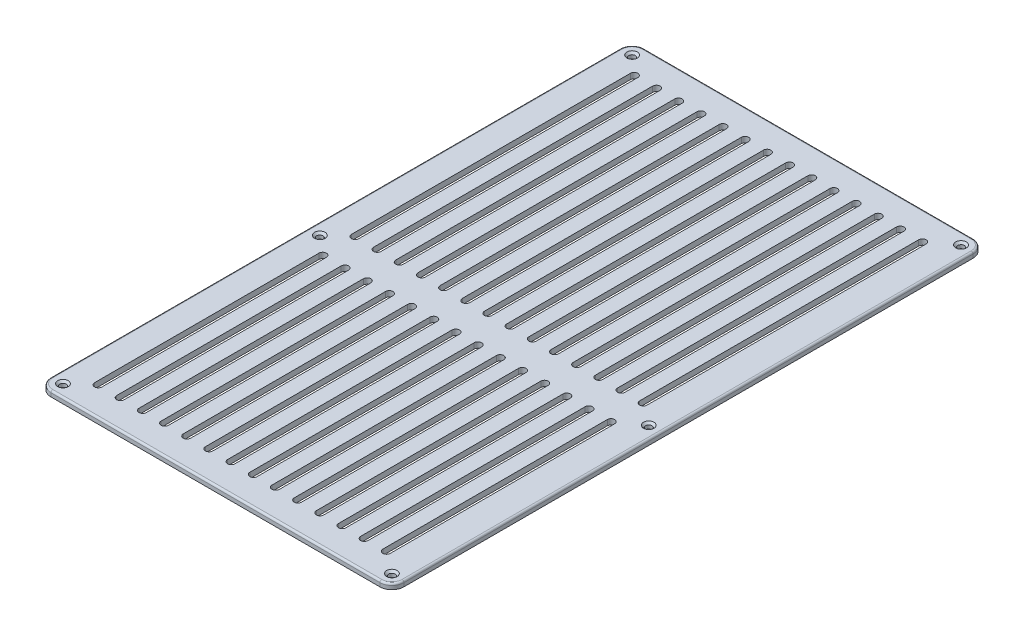
SolidWorks part; units mm, degrees
ref_plane "Front Plane" through (0, 0, 0) normal (0, 0, 1) x (1, 0, 0)
ref_plane "Top Plane" through (0, 0, 0) normal (0, 1, 0) x (1, 0, 0)
ref_plane "Right Plane" through (0, 0, 0) normal (1, 0, 0) x (0, 0, -1)
sketch "Sketch1" plane through (0, 0, 0) normal (0, 1, 0) x (1, 0, 0)
  line L0 (0, 7) -> (0, 315)
  line L1 (7, 322) -> (185, 322)
  line L2 (192, 315) -> (192, 7)
  line L3 (185, 0) -> (7, 0)
  arc A0 (192, 7) -> (185, 0) centre (185, 7) cw
  arc A1 (0, 7) -> (7, 0) centre (7, 7) ccw
  arc A2 (185, 322) -> (192, 315) centre (185, 315) cw
  arc A3 (0, 315) -> (7, 322) centre (7, 315) cw
  circle A4 centre (7, 315) radius 1.75
  circle A5 centre (185, 315) radius 1.75
  circle A6 centre (185, 7) radius 1.75
  circle A7 centre (7, 7) radius 1.75
  circle A8 centre (7, 146) radius 1.75
  circle A9 centre (185, 146) radius 1.75
  point P9 (0, 0)
  dimension "D1" = 7
extrude "Boss-Extrude1" add sketch "Sketch1" along normal blind 3
chamfer "Chamfer1" distance 1.1 angle 45 6 edges at (7, 3, -313.25) (7, 3, -144.25) (7, 3, -5.25) (185, 3, -5.25) (185, 3, -144.25) (185, 3, -313.25)
sketch "Sketch2" plane through (0, 3, 0) normal (0, 1, 0) x (1, 0, 0)
  line L0 (31.1, 306) -> (31.1, 155)
  line L10 (27.1, 306) -> (27.1, 155)
  line L15 (31.1, 16) -> (31.1, 137.46)
  line L16 (27.1, 16) -> (27.1, 137.46)
  line L26 (15.1, 306) -> (15.1, 155)
  line L28 (19.1, 306) -> (19.1, 155)
  line L29 (43.1, 306) -> (43.1, 155)
  line L30 (39.1, 306) -> (39.1, 155)
  line L31 (43.1, 16) -> (43.1, 137.46)
  line L33 (15.1, 16) -> (15.1, 137.46)
  line L35 (19.1, 16) -> (19.1, 137.46)
  line L36 (39.1, 16) -> (39.1, 137.46)
  line L37 (55.1, 306) -> (55.1, 155)
  line L38 (51.1, 306) -> (51.1, 155)
  line L39 (55.1, 16) -> (55.1, 137.46)
  line L40 (51.1, 16) -> (51.1, 137.46)
  line L41 (67.1, 306) -> (67.1, 155)
  line L42 (63.1, 306) -> (63.1, 155)
  line L43 (67.1, 16) -> (67.1, 137.46)
  line L44 (63.1, 16) -> (63.1, 137.46)
  line L45 (79.1, 306) -> (79.1, 155)
  line L46 (75.1, 306) -> (75.1, 155)
  line L47 (79.1, 16) -> (79.1, 137.46)
  line L48 (75.1, 16) -> (75.1, 137.46)
  line L49 (91.1, 306) -> (91.1, 155)
  line L50 (87.1, 306) -> (87.1, 155)
  line L51 (91.1, 16) -> (91.1, 137.46)
  line L52 (87.1, 16) -> (87.1, 137.46)
  line L53 (103.1, 306) -> (103.1, 155)
  line L54 (99.1, 306) -> (99.1, 155)
  line L55 (103.1, 16) -> (103.1, 137.46)
  line L56 (99.1, 16) -> (99.1, 137.46)
  line L57 (115.1, 306) -> (115.1, 155)
  line L58 (111.1, 306) -> (111.1, 155)
  line L59 (115.1, 16) -> (115.1, 137.46)
  line L60 (111.1, 16) -> (111.1, 137.46)
  line L61 (127.1, 306) -> (127.1, 155)
  line L62 (123.1, 306) -> (123.1, 155)
  line L63 (127.1, 16) -> (127.1, 137.46)
  line L64 (123.1, 16) -> (123.1, 137.46)
  line L65 (139.1, 306) -> (139.1, 155)
  line L66 (135.1, 306) -> (135.1, 155)
  line L67 (139.1, 16) -> (139.1, 137.46)
  line L68 (135.1, 16) -> (135.1, 137.46)
  line L69 (151.1, 306) -> (151.1, 155)
  line L70 (147.1, 306) -> (147.1, 155)
  line L71 (151.1, 16) -> (151.1, 137.46)
  line L72 (147.1, 16) -> (147.1, 137.46)
  line L73 (163.1, 306) -> (163.1, 155)
  line L74 (159.1, 306) -> (159.1, 155)
  line L75 (163.1, 16) -> (163.1, 137.46)
  line L76 (159.1, 16) -> (159.1, 137.46)
  line L77 (175.1, 306) -> (175.1, 155)
  line L78 (171.1, 306) -> (171.1, 155)
  line L79 (175.1, 16) -> (175.1, 137.46)
  line L80 (171.1, 16) -> (171.1, 137.46)
  arc A0 (15.1, 155) -> (19.1, 155) centre (17.1, 155) ccw
  arc A1 (19.1, 306) -> (15.1, 306) centre (17.1, 306) ccw
  arc A2 (19.1, 137.46) -> (15.1, 137.46) centre (17.1, 137.46) ccw
  arc A3 (15.1, 16) -> (19.1, 16) centre (17.1, 16) ccw
  arc A4 (27.1, 155) -> (31.1, 155) centre (29.1, 155) ccw
  arc A5 (31.1, 306) -> (27.1, 306) centre (29.1, 306) ccw
  arc A6 (27.1, 16) -> (31.1, 16) centre (29.1, 16) ccw
  arc A7 (31.1, 137.46) -> (27.1, 137.46) centre (29.1, 137.46) ccw
  arc A8 (39.1, 155) -> (43.1, 155) centre (41.1, 155) ccw
  arc A9 (43.1, 306) -> (39.1, 306) centre (41.1, 306) ccw
  arc A10 (39.1, 16) -> (43.1, 16) centre (41.1, 16) ccw
  arc A11 (43.1, 137.46) -> (39.1, 137.46) centre (41.1, 137.46) ccw
  arc A12 (51.1, 155) -> (55.1, 155) centre (53.1, 155) ccw
  arc A13 (55.1, 306) -> (51.1, 306) centre (53.1, 306) ccw
  arc A14 (51.1, 16) -> (55.1, 16) centre (53.1, 16) ccw
  arc A15 (55.1, 137.46) -> (51.1, 137.46) centre (53.1, 137.46) ccw
  arc A16 (63.1, 155) -> (67.1, 155) centre (65.1, 155) ccw
  arc A17 (67.1, 306) -> (63.1, 306) centre (65.1, 306) ccw
  arc A18 (63.1, 16) -> (67.1, 16) centre (65.1, 16) ccw
  arc A19 (67.1, 137.46) -> (63.1, 137.46) centre (65.1, 137.46) ccw
  arc A20 (75.1, 155) -> (79.1, 155) centre (77.1, 155) ccw
  arc A21 (79.1, 306) -> (75.1, 306) centre (77.1, 306) ccw
  arc A22 (75.1, 16) -> (79.1, 16) centre (77.1, 16) ccw
  arc A23 (79.1, 137.46) -> (75.1, 137.46) centre (77.1, 137.46) ccw
  arc A24 (87.1, 155) -> (91.1, 155) centre (89.1, 155) ccw
  arc A25 (91.1, 306) -> (87.1, 306) centre (89.1, 306) ccw
  arc A26 (87.1, 16) -> (91.1, 16) centre (89.1, 16) ccw
  arc A27 (91.1, 137.46) -> (87.1, 137.46) centre (89.1, 137.46) ccw
  arc A28 (99.1, 155) -> (103.1, 155) centre (101.1, 155) ccw
  arc A29 (103.1, 306) -> (99.1, 306) centre (101.1, 306) ccw
  arc A30 (99.1, 16) -> (103.1, 16) centre (101.1, 16) ccw
  arc A31 (103.1, 137.46) -> (99.1, 137.46) centre (101.1, 137.46) ccw
  arc A32 (111.1, 155) -> (115.1, 155) centre (113.1, 155) ccw
  arc A33 (115.1, 306) -> (111.1, 306) centre (113.1, 306) ccw
  arc A34 (111.1, 16) -> (115.1, 16) centre (113.1, 16) ccw
  arc A35 (115.1, 137.46) -> (111.1, 137.46) centre (113.1, 137.46) ccw
  arc A36 (123.1, 155) -> (127.1, 155) centre (125.1, 155) ccw
  arc A37 (127.1, 306) -> (123.1, 306) centre (125.1, 306) ccw
  arc A38 (123.1, 16) -> (127.1, 16) centre (125.1, 16) ccw
  arc A39 (127.1, 137.46) -> (123.1, 137.46) centre (125.1, 137.46) ccw
  arc A40 (135.1, 155) -> (139.1, 155) centre (137.1, 155) ccw
  arc A41 (139.1, 306) -> (135.1, 306) centre (137.1, 306) ccw
  arc A42 (135.1, 16) -> (139.1, 16) centre (137.1, 16) ccw
  arc A43 (139.1, 137.46) -> (135.1, 137.46) centre (137.1, 137.46) ccw
  arc A44 (147.1, 155) -> (151.1, 155) centre (149.1, 155) ccw
  arc A45 (151.1, 306) -> (147.1, 306) centre (149.1, 306) ccw
  arc A46 (147.1, 16) -> (151.1, 16) centre (149.1, 16) ccw
  arc A47 (151.1, 137.46) -> (147.1, 137.46) centre (149.1, 137.46) ccw
  arc A48 (159.1, 155) -> (163.1, 155) centre (161.1, 155) ccw
  arc A49 (163.1, 306) -> (159.1, 306) centre (161.1, 306) ccw
  arc A50 (159.1, 16) -> (163.1, 16) centre (161.1, 16) ccw
  arc A51 (163.1, 137.46) -> (159.1, 137.46) centre (161.1, 137.46) ccw
  arc A52 (171.1, 155) -> (175.1, 155) centre (173.1, 155) ccw
  arc A53 (175.1, 306) -> (171.1, 306) centre (173.1, 306) ccw
  arc A54 (171.1, 16) -> (175.1, 16) centre (173.1, 16) ccw
  arc A55 (175.1, 137.46) -> (171.1, 137.46) centre (173.1, 137.46) ccw
  dimension "D1" = 14
extrude "Cut-Extrude1" cut sketch "Sketch2" against normal blind 38
sketch "Sketch3" plane through (0, 0, 0) normal (0, -1, 0) x (1, 0, 0)
  line L0 (185, -0.5) -> (7, -0.5)
  line L1 (0.5, -7) -> (0.5, -315)
  line L2 (7, -321.5) -> (185, -321.5)
  line L3 (191.5, -315) -> (191.5, -7)
  line L4 (185, 0) -> (7, 0)
  line L5 (0, -7) -> (0, -315)
  line L6 (7, -322) -> (185, -322)
  line L7 (192, -315) -> (192, -7)
  line L8 (185, 0) -> (7, 0)
  line L9 (0, -7) -> (0, -315)
  line L10 (7, -322) -> (185, -322)
  line L11 (192, -315) -> (192, -7)
  arc A0 (191.5, -7) -> (185, -0.5) centre (185, -7) ccw
  arc A1 (7, -0.5) -> (0.5, -7) centre (7, -7) ccw
  arc A2 (0.5, -315) -> (7, -321.5) centre (7, -315) ccw
  arc A3 (185, -321.5) -> (191.5, -315) centre (185, -315) ccw
  arc A4 (192, -7) -> (185, 0) centre (185, -7) ccw
  arc A5 (7, 0) -> (0, -7) centre (7, -7) ccw
  arc A6 (0, -315) -> (7, -322) centre (7, -315) ccw
  arc A7 (185, -322) -> (192, -315) centre (185, -315) ccw
  arc A8 (192, -7) -> (185, 0) centre (185, -7) ccw
  arc A9 (7, 0) -> (0, -7) centre (7, -7) ccw
  arc A10 (0, -315) -> (7, -322) centre (7, -315) ccw
  arc A11 (185, -322) -> (192, -315) centre (185, -315) ccw
  dimension "D1" = 0
  dimension "D2" = 0.5
extrude "Cut-Extrude2" cut sketch "Sketch3" against normal blind 10
fillet "Fillet1" radius 1 8 edges at (189.5962, 3, -319.5962) (96, 3, -321.5) (2.4038, 3, -319.5962) (0.5, 3, -161) (2.4038, 3, -2.4038) (96, 3, -0.5) (189.5962, 3, -2.4038) (191.5, 3, -161)
